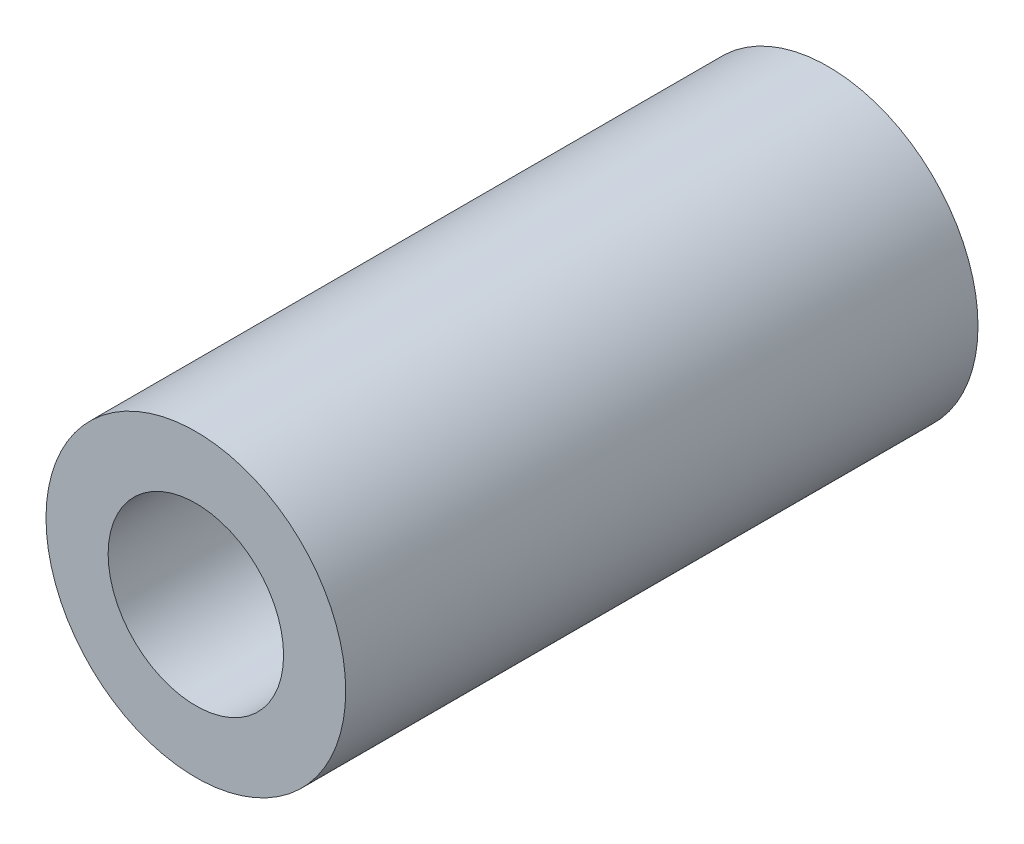
SolidWorks part; units mm, degrees
ref_plane "Front Plane" through (0, 0, 0) normal (0, 0, 1) x (1, 0, 0)
ref_plane "Top Plane" through (0, 0, 0) normal (0, 1, 0) x (1, 0, 0)
ref_plane "Right Plane" through (0, 0, 0) normal (1, 0, 0) x (0, 0, -1)
sketch "Sketch1" plane through (0, 0, 0) normal (0, 0, 1) x (1, 0, 0)
  circle A0 centre (0, 0) radius 20.5
  circle A1 centre (0, 0) radius 12
  dimension "D1" = 41
  dimension "D2" = 24
extrude "Boss-Extrude1" add sketch "Sketch1" along normal blind 36 and the other way blind 50.5
equation "\"D2@Boss-Extrude1\"=86.5/2"
equation "\"D1@Boss-Extrude1\"=86.5/2"
